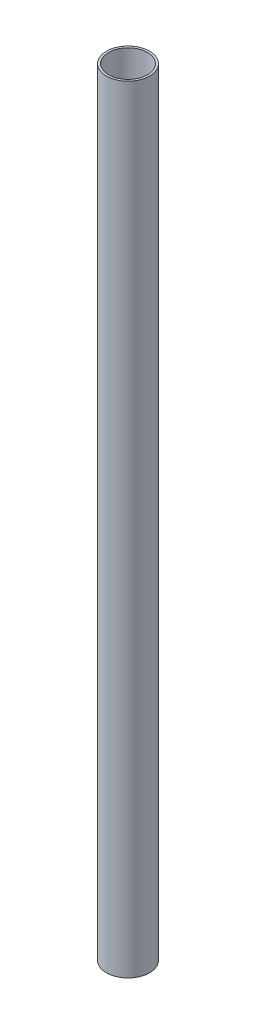
SolidWorks part; units mm, degrees
ref_plane "前视基准面" through (0, 0, 0) normal (0, 0, 1) x (1, 0, 0)
ref_plane "上视基准面" through (0, 0, 0) normal (0, 1, 0) x (1, 0, 0)
ref_plane "右视基准面" through (0, 0, 0) normal (1, 0, 0) x (0, 0, -1)
sketch "草图1" plane through (0, 0, 0) normal (0, 1, 0) x (1, 0, 0)
  circle A0 centre (0, 0) radius 10
  dimension "D1" = 20
extrude "1mm*40" add sketch "草图1" along normal mid plane 360 thin thin type one direction reverse wall 1
